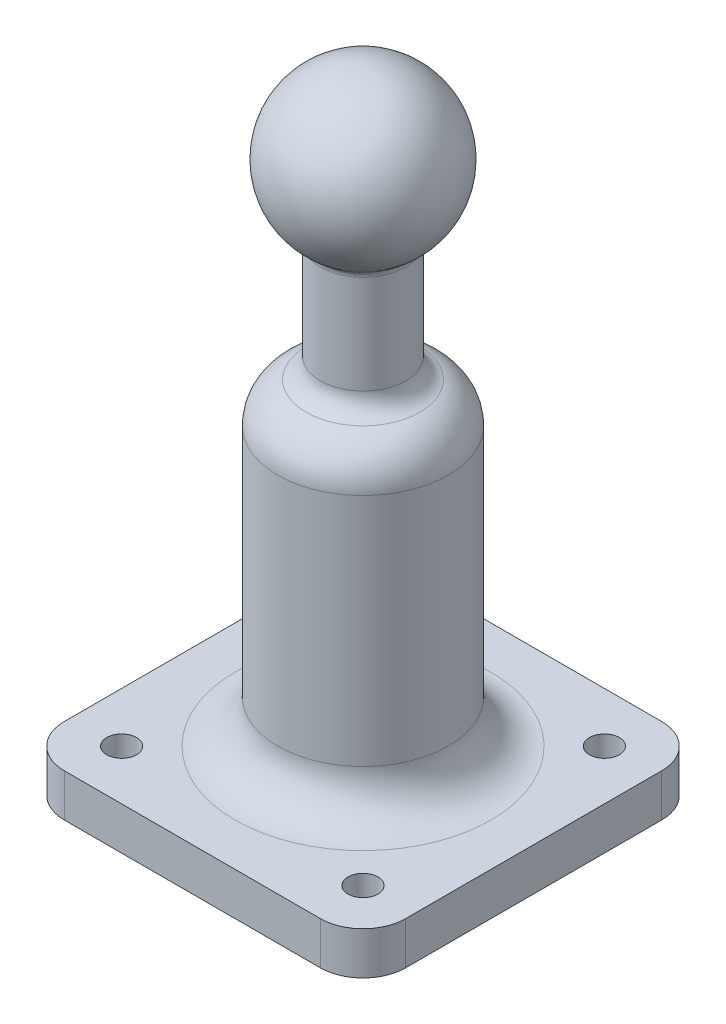
SolidWorks part; units mm, degrees
material "ABS"
ref_plane "Front Plane" through (0, 0, 0) normal (0, 0, 1) x (1, 0, 0)
ref_plane "Top Plane" through (0, 0, 0) normal (0, 1, 0) x (1, 0, 0)
ref_plane "Right Plane" through (0, 0, 0) normal (1, 0, 0) x (0, 0, -1)
sketch "Sketch1" plane through (0, 0, 0) normal (0, 1, 0) x (1, 0, 0)
  line L1 (-30, 40) -> (30, 40)
  line L2 (-40, 30) -> (-40, -30)
  line L3 (-30, -40) -> (30, -40)
  line L4 (40, 30) -> (40, -30)
  line L5 (-40, 40) -> (40, -40) construction
  line L6 (-40, -40) -> (40, 40) construction
  circle A0 centre (0, 0) radius 40 construction
  circle A1 centre (-28.2843, 28.2843) radius 3.5
  circle A2 centre (28.2843, 28.2843) radius 3.5
  circle A3 centre (28.2843, -28.2843) radius 3.5
  circle A4 centre (-28.2843, -28.2843) radius 3.5
  arc A5 (-40, -30) -> (-30, -40) centre (-30, -30) ccw
  arc A6 (30, -40) -> (40, -30) centre (30, -30) ccw
  arc A7 (30, 40) -> (40, 30) centre (30, 30) cw
  arc A8 (-30, 40) -> (-40, 30) centre (-30, 30) ccw
  point P0 (0, 0)
  dimension "D2" = 7
  dimension "D3" = 10
  dimension "D1" = 80
extrude "Boss-Extrude1" add sketch "Sketch1" along normal blind 10
sketch "Sketch2" plane through (0, 10, 0) normal (0, 1, 0) x (1, 0, 0)
  circle A0 centre (0, 0) radius 20
  dimension "D1" = 40
extrude "Boss-Extrude2" add sketch "Sketch2" along normal blind 75
fillet "Fillet1" radius 10 2 edges at (0, 10, 20) (0, 85, 20)
sketch "Sketch3" plane through (0, 85, 0) normal (0, 1, 0) x (1, 0, 0)
  circle A0 centre (0, 0) radius 10
  dimension "D1" = 20
extrude "Boss-Extrude3" add sketch "Sketch3" along normal blind 30
fillet "Fillet2" radius 5 1 edges at (0, 85, 10)
sketch "Sketch4" plane through (0, 0, 0) normal (0, 0, 1) x (1, 0, 0)
  line L0 (0, 115) -> (0, 129.1421) construction
  line L1 (10, 115) -> (-10, 115) construction
  line L2 (0, 110.3921) -> (0, 147.8921)
  line L3 (10, 89.1421) -> (-10, 89.1421) construction
  arc A0 (0, 110.3921) -> (0, 147.8921) centre (0, 129.1421) ccw
  arc A1 (0, 147.8921) -> (0, 110.3921) centre (0, 129.1421) ccw construction
  dimension "D1" = 18.75
  dimension "D2" = 40
revolve "Revolve1" add sketch "Sketch4" angle 360 about L0
fillet "Fillet3" radius 2 1 edges at (0, 113.2814, 10)
